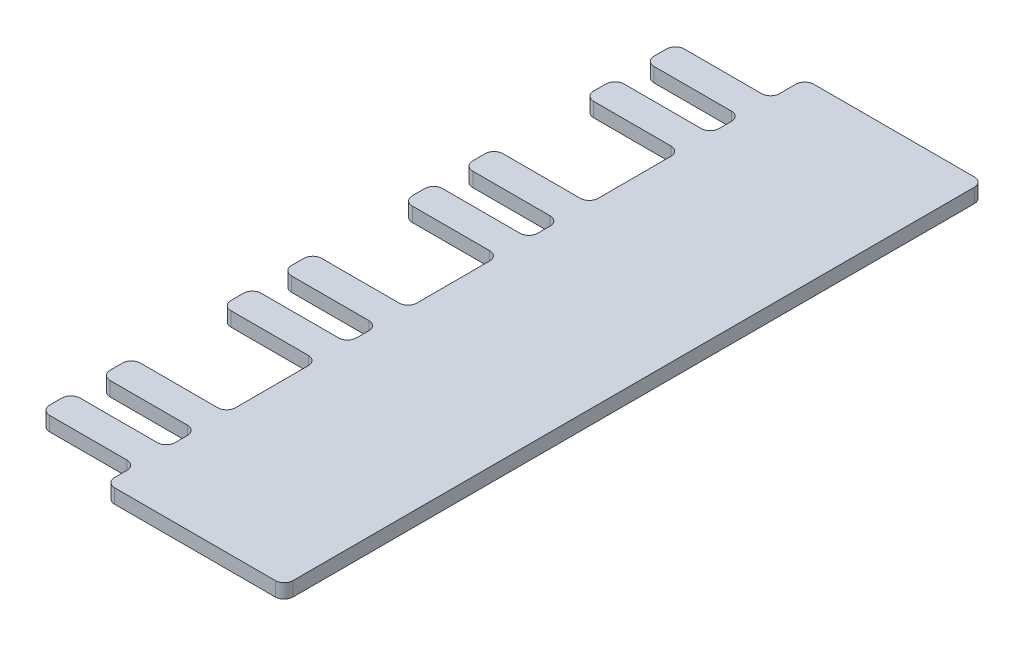
SolidWorks part; units mm, degrees
ref_plane "Front Plane" through (0, 0, 0) normal (0, 0, 1) x (1, 0, 0)
ref_plane "Top Plane" through (0, 0, 0) normal (0, 1, 0) x (1, 0, 0)
ref_plane "Right Plane" through (0, 0, 0) normal (1, 0, 0) x (0, 0, -1)
sketch "Sketch1" plane through (0, 0, 0) normal (0, 1, 0) x (1, 0, 0)
  line L0 (-0.75, 2.54) -> (-7.25, 2.54)
  line L2 (0, 1.79) -> (0, 0.75)
  line L5 (-8, 3.81) -> (5.7163, 3.81) construction
  line L7 (-8, 3.29) -> (-8, 4.33)
  line L8 (-7.25, 5.08) -> (-0.75, 5.08)
  line L12 (0, 6.87) -> (0, 5.83)
  line L17 (-0.75, 7.62) -> (-7.25, 7.62)
  line L22 (-8, 8.37) -> (-8, 9.41)
  line L27 (-7.25, 10.16) -> (-0.75, 10.16)
  line L56 (14.25, 0) -> (0.75, 0)
  line L84 (0, 11.95) -> (0, 10.91) [skipped]
  line L85 (-0.75, 12.7) -> (-7.25, 12.7) [skipped]
  line L86 (-8, 13.45) -> (-8, 14.49) [skipped]
  line L87 (-7.25, 15.24) -> (-0.75, 15.24) [skipped]
  line L88 (0, 17.03) -> (0, 15.99) [skipped]
  line L89 (-0.75, 17.78) -> (-7.25, 17.78) [skipped]
  line L90 (-8, 18.53) -> (-8, 19.57) [skipped]
  line L91 (-7.25, 20.32) -> (-0.75, 20.32) [skipped]
  line L92 (0, 22.11) -> (0, 21.07) [skipped]
  line L93 (-0.75, 22.86) -> (-7.25, 22.86) [skipped]
  line L94 (-8, 23.61) -> (-8, 24.65) [skipped]
  line L95 (-7.25, 25.4) -> (-0.75, 25.4) [skipped]
  line L96 (0, 27.19) -> (0, 26.15) [skipped]
  line L97 (-0.75, 27.94) -> (-7.25, 27.94) [skipped]
  line L98 (-8, 28.69) -> (-8, 29.73) [skipped]
  line L99 (-7.25, 30.48) -> (-0.75, 30.48) [skipped]
  line L100 (0, 32.27) -> (0, 31.23) [skipped]
  line L101 (-0.75, 33.02) -> (-7.25, 33.02) [skipped]
  line L102 (-8, 33.77) -> (-8, 34.81) [skipped]
  line L103 (-7.25, 35.56) -> (-0.75, 35.56) [skipped]
  line L104 (0, 37.35) -> (0, 36.31) [skipped]
  line L105 (-0.75, 38.1) -> (-7.25, 38.1) [skipped]
  line L106 (-8, 38.85) -> (-8, 39.89) [skipped]
  line L107 (-7.25, 40.64) -> (-0.75, 40.64) [skipped]
  line L108 (0, 42.43) -> (0, 41.39) [skipped]
  line L109 (-0.75, 43.18) -> (-7.25, 43.18) [skipped]
  line L110 (-8, 43.93) -> (-8, 44.97) [skipped]
  line L111 (-7.25, 45.72) -> (-0.75, 45.72) [skipped]
  line L112 (0, 47.51) -> (0, 46.47) [skipped]
  line L113 (-0.75, 48.26) -> (-7.25, 48.26) [skipped]
  line L114 (-8, 49.01) -> (-8, 50.05) [skipped]
  line L115 (-7.25, 50.8) -> (-0.75, 50.8) [skipped]
  line L116 (-0.75, 17.78) -> (-7.25, 17.78)
  line L117 (-8, 18.53) -> (-8, 19.57)
  line L118 (-7.25, 20.32) -> (-0.75, 20.32)
  line L119 (0, 22.11) -> (0, 21.07)
  line L120 (-0.75, 22.86) -> (-7.25, 22.86)
  line L121 (-8, 23.61) -> (-8, 24.65)
  line L122 (-7.25, 25.4) -> (-0.75, 25.4)
  line L123 (-0.75, 33.02) -> (-7.25, 33.02)
  line L124 (-8, 33.77) -> (-8, 34.81)
  line L125 (-7.25, 35.56) -> (-0.75, 35.56)
  line L126 (0, 37.35) -> (0, 36.31)
  line L127 (-0.75, 38.1) -> (-7.25, 38.1)
  line L128 (-8, 38.85) -> (-8, 39.89)
  line L129 (-7.25, 40.64) -> (-0.75, 40.64)
  line L130 (-0.75, 48.26) -> (-7.25, 48.26)
  line L131 (-8, 49.01) -> (-8, 50.05)
  line L132 (-7.25, 50.8) -> (-0.75, 50.8)
  line L133 (0, 52.59) -> (0, 51.55)
  line L134 (-0.75, 53.34) -> (-7.25, 53.34)
  line L135 (-8, 54.09) -> (-8, 55.13)
  line L136 (-7.25, 55.88) -> (-0.75, 55.88)
  line L137 (0, 17.03) -> (0, 10.91)
  line L138 (0, 26.15) -> (0, 32.27)
  line L139 (0, 41.39) -> (0, 47.51)
  line L140 (0, 56.63) -> (0, 58.0068)
  line L141 (0.75, 58.7568) -> (14.25, 58.7568)
  line L142 (15, 58.0068) -> (15, 0.75)
  arc A0 (-0.75, 5.08) -> (0, 5.83) centre (-0.75, 5.83) ccw
  arc A1 (-8, 4.33) -> (-7.25, 5.08) centre (-7.25, 4.33) cw
  arc A2 (-7.25, 2.54) -> (-8, 3.29) centre (-7.25, 3.29) cw
  arc A3 (0, 0.75) -> (0.75, 0) centre (0.75, 0.75) ccw
  arc A4 (-0.75, 2.54) -> (0, 1.79) centre (-0.75, 1.79) cw
  arc A5 (15, 0.75) -> (14.25, 0) centre (14.25, 0.75) cw
  arc A6 (-0.75, 7.62) -> (0, 6.87) centre (-0.75, 6.87) cw
  arc A7 (-7.25, 7.62) -> (-8, 8.37) centre (-7.25, 8.37) cw
  arc A8 (-8, 9.41) -> (-7.25, 10.16) centre (-7.25, 9.41) cw
  arc A9 (-0.75, 10.16) -> (0, 10.91) centre (-0.75, 10.91) ccw
  arc A44 (-0.75, 12.7) -> (0, 11.95) centre (-0.75, 11.95) cw [skipped]
  arc A45 (-7.25, 12.7) -> (-8, 13.45) centre (-7.25, 13.45) cw [skipped]
  arc A46 (-8, 14.49) -> (-7.25, 15.24) centre (-7.25, 14.49) cw [skipped]
  arc A47 (-0.75, 15.24) -> (0, 15.99) centre (-0.75, 15.99) ccw [skipped]
  arc A48 (-0.75, 17.78) -> (0, 17.03) centre (-0.75, 17.03) cw [skipped]
  arc A49 (-7.25, 17.78) -> (-8, 18.53) centre (-7.25, 18.53) cw [skipped]
  arc A50 (-8, 19.57) -> (-7.25, 20.32) centre (-7.25, 19.57) cw [skipped]
  arc A51 (-0.75, 20.32) -> (0, 21.07) centre (-0.75, 21.07) ccw [skipped]
  arc A52 (-0.75, 22.86) -> (0, 22.11) centre (-0.75, 22.11) cw [skipped]
  arc A53 (-7.25, 22.86) -> (-8, 23.61) centre (-7.25, 23.61) cw [skipped]
  arc A54 (-8, 24.65) -> (-7.25, 25.4) centre (-7.25, 24.65) cw [skipped]
  arc A55 (-0.75, 25.4) -> (0, 26.15) centre (-0.75, 26.15) ccw [skipped]
  arc A56 (-0.75, 27.94) -> (0, 27.19) centre (-0.75, 27.19) cw [skipped]
  arc A57 (-7.25, 27.94) -> (-8, 28.69) centre (-7.25, 28.69) cw [skipped]
  arc A58 (-8, 29.73) -> (-7.25, 30.48) centre (-7.25, 29.73) cw [skipped]
  arc A59 (-0.75, 30.48) -> (0, 31.23) centre (-0.75, 31.23) ccw [skipped]
  arc A60 (-0.75, 33.02) -> (0, 32.27) centre (-0.75, 32.27) cw [skipped]
  arc A61 (-7.25, 33.02) -> (-8, 33.77) centre (-7.25, 33.77) cw [skipped]
  arc A62 (-8, 34.81) -> (-7.25, 35.56) centre (-7.25, 34.81) cw [skipped]
  arc A63 (-0.75, 35.56) -> (0, 36.31) centre (-0.75, 36.31) ccw [skipped]
  arc A64 (-0.75, 38.1) -> (0, 37.35) centre (-0.75, 37.35) cw [skipped]
  arc A65 (-7.25, 38.1) -> (-8, 38.85) centre (-7.25, 38.85) cw [skipped]
  arc A66 (-8, 39.89) -> (-7.25, 40.64) centre (-7.25, 39.89) cw [skipped]
  arc A67 (-0.75, 40.64) -> (0, 41.39) centre (-0.75, 41.39) ccw [skipped]
  arc A68 (-0.75, 43.18) -> (0, 42.43) centre (-0.75, 42.43) cw [skipped]
  arc A69 (-7.25, 43.18) -> (-8, 43.93) centre (-7.25, 43.93) cw [skipped]
  arc A70 (-8, 44.97) -> (-7.25, 45.72) centre (-7.25, 44.97) cw [skipped]
  arc A71 (-0.75, 45.72) -> (0, 46.47) centre (-0.75, 46.47) ccw [skipped]
  arc A72 (-0.75, 48.26) -> (0, 47.51) centre (-0.75, 47.51) cw [skipped]
  arc A73 (-7.25, 48.26) -> (-8, 49.01) centre (-7.25, 49.01) cw [skipped]
  arc A74 (-8, 50.05) -> (-7.25, 50.8) centre (-7.25, 50.05) cw [skipped]
  arc A75 (-0.75, 50.8) -> (0, 51.55) centre (-0.75, 51.55) ccw [skipped]
  arc A76 (-0.75, 20.32) -> (0, 21.07) centre (-0.75, 21.07) ccw
  arc A77 (-8, 19.57) -> (-7.25, 20.32) centre (-7.25, 19.57) cw
  arc A78 (-7.25, 17.78) -> (-8, 18.53) centre (-7.25, 18.53) cw
  arc A79 (-0.75, 17.78) -> (0, 17.03) centre (-0.75, 17.03) cw
  arc A80 (-0.75, 22.86) -> (0, 22.11) centre (-0.75, 22.11) cw
  arc A81 (-7.25, 22.86) -> (-8, 23.61) centre (-7.25, 23.61) cw
  arc A82 (-8, 24.65) -> (-7.25, 25.4) centre (-7.25, 24.65) cw
  arc A83 (-0.75, 25.4) -> (0, 26.15) centre (-0.75, 26.15) ccw
  arc A84 (-0.75, 35.56) -> (0, 36.31) centre (-0.75, 36.31) ccw
  arc A85 (-8, 34.81) -> (-7.25, 35.56) centre (-7.25, 34.81) cw
  arc A86 (-7.25, 33.02) -> (-8, 33.77) centre (-7.25, 33.77) cw
  arc A87 (-0.75, 33.02) -> (0, 32.27) centre (-0.75, 32.27) cw
  arc A88 (-0.75, 38.1) -> (0, 37.35) centre (-0.75, 37.35) cw
  arc A89 (-7.25, 38.1) -> (-8, 38.85) centre (-7.25, 38.85) cw
  arc A90 (-8, 39.89) -> (-7.25, 40.64) centre (-7.25, 39.89) cw
  arc A91 (-0.75, 40.64) -> (0, 41.39) centre (-0.75, 41.39) ccw
  arc A92 (-0.75, 50.8) -> (0, 51.55) centre (-0.75, 51.55) ccw
  arc A93 (-8, 50.05) -> (-7.25, 50.8) centre (-7.25, 50.05) cw
  arc A94 (-7.25, 48.26) -> (-8, 49.01) centre (-7.25, 49.01) cw
  arc A95 (-0.75, 48.26) -> (0, 47.51) centre (-0.75, 47.51) cw
  arc A96 (-0.75, 53.34) -> (0, 52.59) centre (-0.75, 52.59) cw
  arc A97 (-7.25, 53.34) -> (-8, 54.09) centre (-7.25, 54.09) cw
  arc A98 (-8, 55.13) -> (-7.25, 55.88) centre (-7.25, 55.13) cw
  arc A99 (-0.75, 55.88) -> (0, 56.63) centre (-0.75, 56.63) ccw
  arc A100 (0, 58.0068) -> (0.75, 58.7568) centre (0.75, 58.0068) cw
  arc A101 (14.25, 58.7568) -> (15, 58.0068) centre (14.25, 58.0068) cw
  point P0 (0, 0)
  point P27 (0, 5.08)
  point P46 (0, 20.32)
  point P48 (-8, 5.08)
  point P69 (-8, 2.54)
  point P73 (0, 35.56)
  point P78 (0, 0)
  point P81 (0, 2.54)
  point P84 (15, 0)
  point P108 (0, 50.8)
  dimension "D6" = 0.75
  dimension "D7" = 0.75
  dimension "D8" = 4
  dimension "D9" = 10.16
  dimension "D11" = 0.75
  dimension "D1" = 2.54
  dimension "D2" = 8
  dimension "D3" = 10
  dimension "D4" = 2.54
  dimension "D5" = 15
  dimension "D10" = 5.08
extrude "Boss-Extrude1" add sketch "Sketch1" along normal blind 1.2
